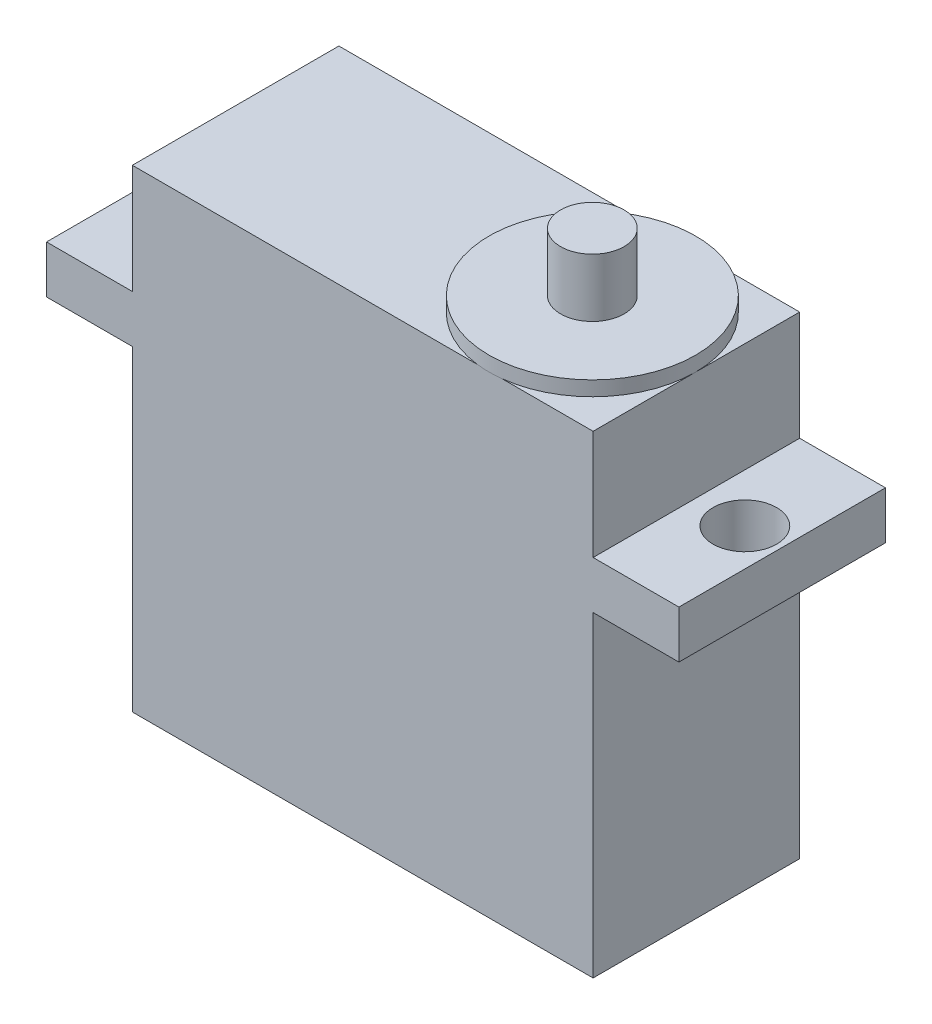
SolidWorks part; units mm, degrees
ref_plane "Front Plane" through (0, 0, 0) normal (0, 0, 1) x (1, 0, 0)
ref_plane "Top Plane" through (0, 0, 0) normal (0, 1, 0) x (1, 0, 0)
ref_plane "Right Plane" through (0, 0, 0) normal (1, 0, 0) x (0, 0, -1)
sketch "Sketch1" plane through (0, 0, 0) normal (0, 1, 0) x (1, 0, 0)
  line L1 (0, 0) -> (29, 0)
  line L2 (0, 0) -> (0, 13)
  line L3 (0, 13) -> (29, 13)
  line L4 (29, 0) -> (29, 13)
  dimension "D1" = 13
  dimension "D2" = 29
extrude "Boss-Extrude1" add sketch "Sketch1" along normal blind 19.92
sketch "Sketch2" plane through (0, 19.92, 0) normal (0, 1, 0) x (1, 0, 0)
  line L0 (29, 13) -> (0, 13) construction
  line L1 (-5.4, 13) -> (34.4, 13)
  line L2 (-5.4, 13) -> (-5.4, 0)
  line L3 (-5.4, 0) -> (34.4, 0)
  line L4 (34.4, 13) -> (34.4, 0)
  line L5 (14.5, 13) -> (14.5, 0) construction
  line L6 (0, 0) -> (29, 0) construction
  line L7 (-5.4, 6.5) -> (34.4, 6.5) construction
  circle A0 centre (-3.05, 6.5) radius 2
  circle A1 centre (32.05, 6.5) radius 2
  point P16 (-2.947, 6.5)
  dimension "D5" = 4
  dimension "D1" = 13
  dimension "D2" = 39.8
  dimension "D3" = 19.9
  dimension "D4" = 35.1
  dimension "D6" = 17.55
extrude "Boss-Extrude2" add sketch "Sketch2" along normal blind 3
sketch "Sketch3" plane through (0, 22.92, 0) normal (0, 1, 0) x (1, 0, 0)
  line L0 (14.5, 13) -> (14.5, 0) construction
  line L1 (34.4, 13) -> (-5.4, 13) construction
  line L2 (-5.4, 0) -> (34.4, 0) construction
  line L3 (-5.4, 6.5) -> (34.4, 6.5) construction
  line L4 (-5.4, 13) -> (-5.4, 0) construction
  line L5 (34.4, 0) -> (34.4, 13) construction
  line L7 (0, 0) -> (29, 0)
  line L8 (0, 0) -> (0, 13)
  line L9 (0, 13) -> (29, 13)
  line L10 (29, 0) -> (29, 13)
  line L11 (0, 0) -> (29, 13) construction
  line L12 (0, 13) -> (29, 0) construction
  point P12 (14.5, 6.5)
  dimension "D1" = 29
extrude "Boss-Extrude3" add sketch "Sketch3" along normal blind 6.88
sketch "Sketch4" plane through (0, 29.8, 0) normal (0, 1, 0) x (1, 0, 0)
  line L0 (29, 0) -> (29, 13) construction
  circle A0 centre (22.5, 6.4528) radius 6.5
  dimension "D1" = 13
extrude "Boss-Extrude4" add sketch "Sketch4" along normal blind 0.92
sketch "Sketch5" plane through (0, 30.72, 0) normal (0, 1, 0) x (1, 0, 0)
  circle A0 centre (22.5, 6.4528) radius 2
  dimension "D1" = 4
extrude "Boss-Extrude5" add sketch "Sketch5" along normal blind 3.67
